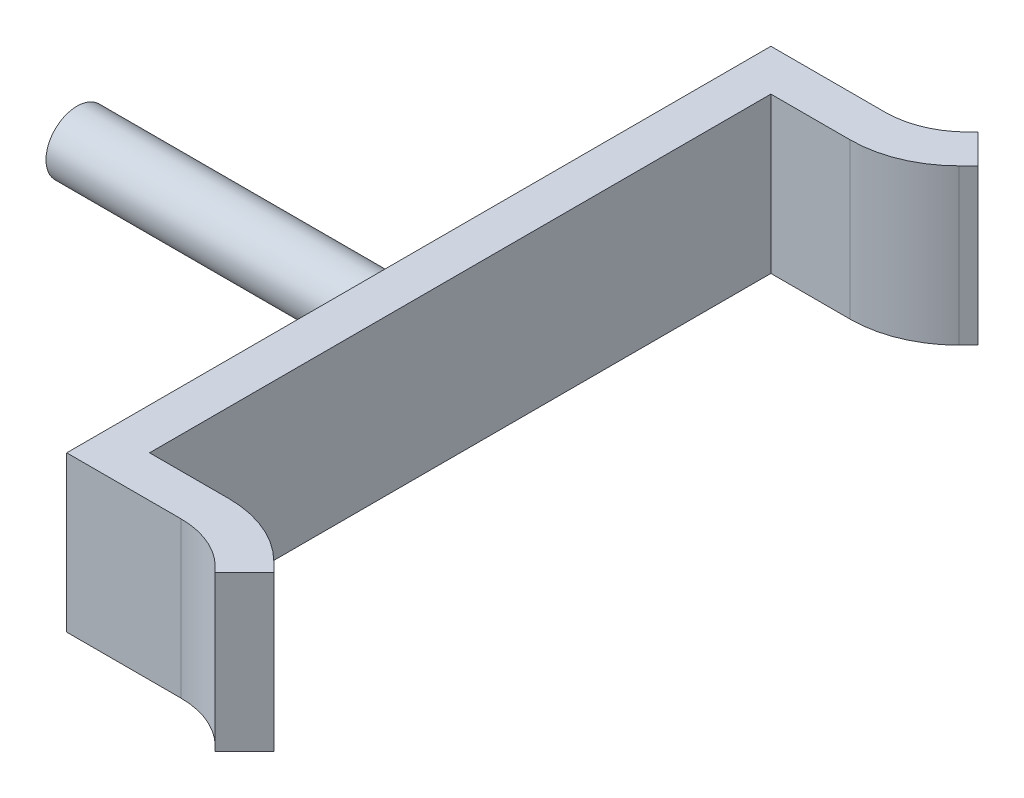
SolidWorks part; units mm, degrees
ref_plane "Front Plane" through (0, 0, 0) normal (0, 0, 1) x (1, 0, 0)
ref_plane "Top Plane" through (0, 0, 0) normal (0, 1, 0) x (1, 0, 0)
ref_plane "Right Plane" through (0, 0, 0) normal (1, 0, 0) x (0, 0, -1)
sketch "Sketch1" plane through (0, 0, 0) normal (0, 1, 0) x (1, 0, 0)
  line L0 (0, -34) -> (0, 34)
  line L1 (0, 34) -> (11.0294, 34)
  line L2 (16.6863, 36.3431) -> (17.1716, 36.8284)
  line L3 (17.1716, 36.8284) -> (20, 34)
  line L4 (20, 34) -> (19.0754, 33.0754)
  line L5 (11.6508, 30) -> (4, 30)
  line L6 (4, 30) -> (4, -30)
  line L7 (4, 0) -> (0, 0)
  line L8 (0, -34) -> (11.0294, -34)
  line L9 (16.6863, -36.3431) -> (17.1716, -36.8284)
  line L10 (17.1716, -36.8284) -> (20, -34)
  line L11 (20, -34) -> (19.0754, -33.0754)
  line L12 (11.6508, -30) -> (4, -30)
  arc A0 (19.0754, 33.0754) -> (11.6508, 30) centre (11.6508, 40.5) cw
  arc A1 (11.0294, 34) -> (16.6863, 36.3431) centre (11.0294, 42) ccw
  arc A2 (11.0294, -34) -> (16.6863, -36.3431) centre (11.0294, -42) cw
  arc A3 (19.0754, -33.0754) -> (11.6508, -30) centre (11.6508, -40.5) ccw
  point P11 (16, 30)
  dimension "D6" = 16
  dimension "D8" = 10.5
  dimension "D9" = 8
  dimension "D1" = 4
  dimension "D2" = 30
  dimension "D3" = 4
  dimension "D4" = 4
  dimension "D5" = 135
  dimension "D7" = 12
extrude "Boss-Extrude2" add sketch "Sketch1" along normal blind 15 contours A1 L1 L0 L7 L6 L5 A0 L4 L3 L2 | L11 A3 L12 L6 L7 L0 L8 A2 L9 L10
sketch "Sketch3" plane through (0, 0, 0) normal (-1, 0, 0) x (0, 0, 1)
  line L0 (-34, 0) -> (34, 15)
  line L1 (34, 0) -> (-34, 15)
  line L4 (-34, 0) -> (34, 0)
  line L5 (34, 0) -> (34, 15)
  line L6 (34, 15) -> (-34, 15)
  line L7 (-34, 15) -> (-34, 0)
  line L8 (-34, 0) -> (34, 0)
  line L9 (34, 0) -> (34, 15)
  line L10 (34, 15) -> (-34, 15)
  line L11 (-34, 15) -> (-34, 0)
  circle A0 centre (0, 7.5) radius 3
  point P5 (0, 7.5)
  point P7 (0, 7.5)
  dimension "D2" = 6
  dimension "D1" = 0
extrude "Boss-Extrude3" add sketch "Sketch3" along normal blind 33 contours A0
